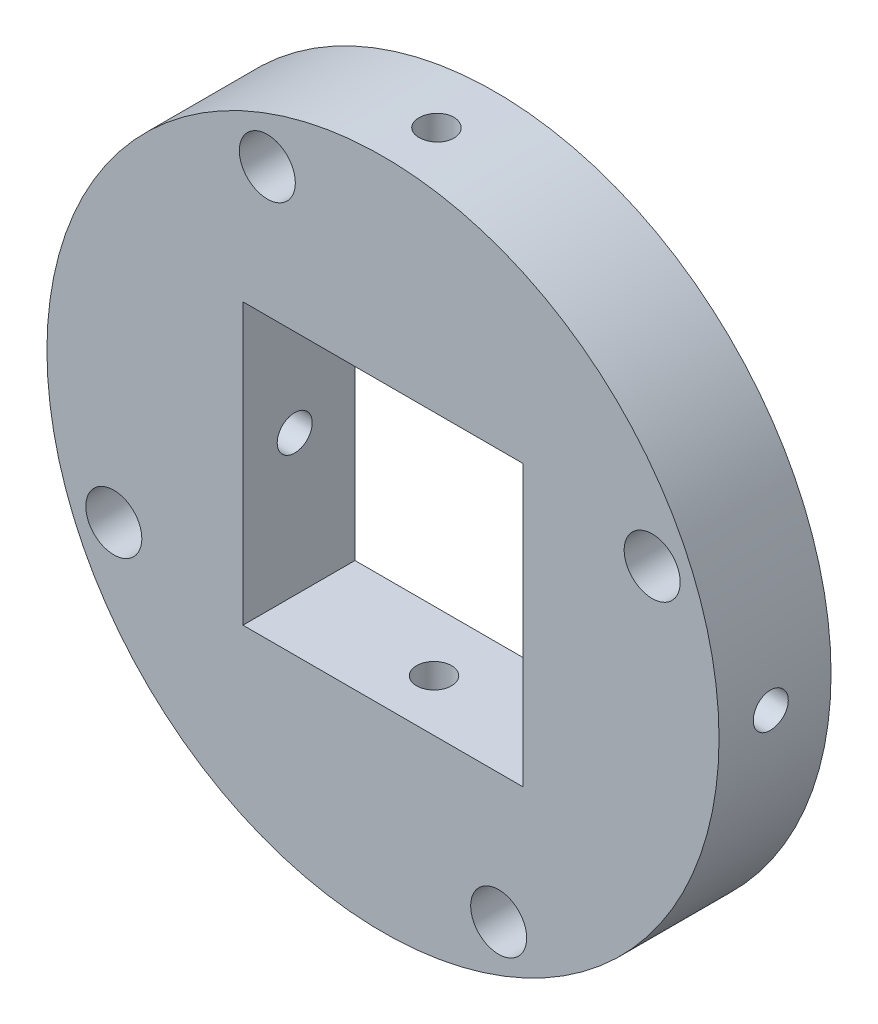
SolidWorks part; units mm, degrees
ref_plane "Front Plane" through (0, 0, 0) normal (0, 0, 1) x (1, 0, 0)
ref_plane "Top Plane" through (0, 0, 0) normal (0, 1, 0) x (1, 0, 0)
ref_plane "Right Plane" through (0, 0, 0) normal (1, 0, 0) x (0, 0, -1)
sketch "Sketch1" plane through (0, 0, 0) normal (0, 0, 1) x (1, 0, 0)
  circle A0 centre (0, 0) radius 7.62
  dimension "D1" = 15.24
extrude "Boss-Extrude1" add sketch "Sketch1" along normal blind 2.54
sketch "Sketch2" plane through (0, 0, 2.54) normal (0, 0, 1) x (1, 0, 0)
  line L1 (-3.175, 3.175) -> (3.175, 3.175)
  line L2 (-3.175, 3.175) -> (-3.175, -3.175)
  line L3 (-3.175, -3.175) -> (3.175, -3.175)
  line L4 (3.175, 3.175) -> (3.175, -3.175)
  line L5 (-3.175, 3.175) -> (3.175, -3.175) construction
  line L6 (-3.175, -3.175) -> (3.175, 3.175) construction
  point P0 (0, 0)
  dimension "D1" = 6.35
  dimension "D2" = 6.35
extrude "Cut-Extrude1" cut sketch "Sketch2" against normal through all
sketch "Sketch3" plane through (0, 0, 2.54) normal (0, 0, 1) x (1, 0, 0)
  circle A0 centre (-2.6227, 6.1035) radius 0.635
  dimension "D1" = 1.27
extrude "Cut-Extrude2" cut sketch "Sketch3" against normal through all contours A0
pattern_circular "CirPattern1" count 4 every 90 about axis through (0, 0, 0) along (0, 0, 1) of "Cut-Extrude2"
ref_plane "Plane1" through (0, 7.62, 0) normal (0, 1, 0) x (1, 0, 0)
hole_wizard "1/32 (0.03125) Diameter Hole1" positions "3DSketch1" profile "Sketch6" hole size "1/32" standard "ANSI Inch"
sketch3d "3DSketch1"
  point P0 (0.0387, 7.6199, 1.3668)
sketch "Sketch6" plane through (0.0387, 7.6199, 1.3668) normal (0, 0, 1) x (-1, 0.0051, 0)
  line L0 (0, 0) -> (0, 6.683)
  line L1 (0, 6.683) -> (0.3969, 6.35)
  line L2 (0.3969, 6.35) -> (0.3969, 0)
  line L5 (0.3969, 0) -> (0, 0)
  line L10 (0, 6.683) -> (-0.3969, 6.35) construction
  line L11 (0, -6.35) -> (0, 107.95) construction
  dimension "Hole Dia." = 0.7937
  dimension "Hole Depth" = 6.35
  dimension "Drill Angle" = 100
pattern_circular "CirPattern2" count 4 every 90 about axis through (0, 0, 2.54) along (0, 0, -1) of "1/32 (0.03125) Diameter Hole1"
